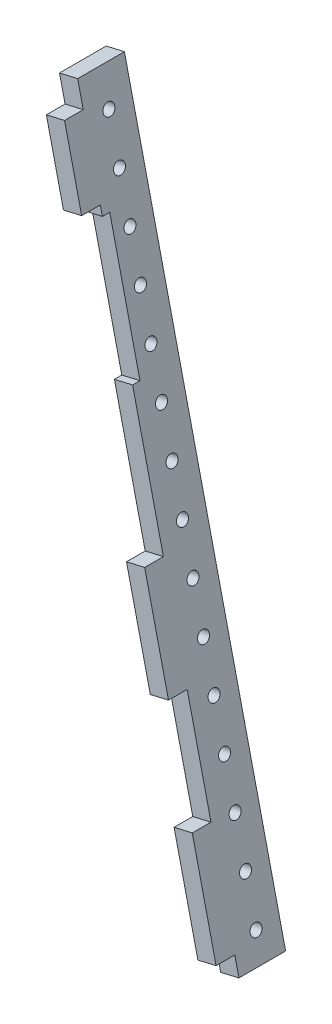
SolidWorks part; units mm, degrees
ref_plane "Front Plane" through (0, 0, 0) normal (0, 0, 1) x (1, 0, 0)
ref_plane "Top Plane" through (0, 0, 0) normal (0, 1, 0) x (1, 0, 0)
ref_plane "Right Plane" through (0, 0, 0) normal (1, 0, 0) x (0, 0, -1)
sketch "Sketch1" plane through (0, 0, 0) normal (0, 0, 1) x (1, 0, 0)
  line L0 (-117.4836, 1583.6084) -> (-107.584, 1585.8939) construction
  line L1 (-81.7027, 1473.7898) -> (-94.6434, 1529.8418) construction
  line L2 (-91.6023, 1471.5043) -> (-81.7027, 1473.7898) construction
  line L3 (-91.6023, 1471.5043) -> (-104.543, 1527.5563) construction
  line L4 (-104.543, 1527.5563) -> (-94.6434, 1529.8418) construction
  line L5 (-120.5247, 1641.946) -> (-107.584, 1585.8939) construction
  line L6 (-130.4243, 1639.6605) -> (-117.4836, 1583.6084) construction
  line L7 (-130.4243, 1639.6605) -> (-120.5247, 1641.946) construction
  line L8 (-120.5247, 1641.946) -> (-107.584, 1585.8939)
  line L9 (-130.4243, 1639.6605) -> (-120.5247, 1641.946)
  line L10 (-130.4243, 1639.6605) -> (-117.4836, 1583.6084)
  line L11 (-117.4836, 1583.6084) -> (-107.584, 1585.8939)
  line L12 (-104.543, 1527.5563) -> (-94.6434, 1529.8418)
  line L13 (-91.6023, 1471.5043) -> (-81.7027, 1473.7898)
  line L14 (-91.6023, 1471.5043) -> (-104.543, 1527.5563)
  line L15 (-81.7027, 1473.7898) -> (-94.6434, 1529.8418)
  line L16 (-81.7027, 1473.7898) -> (-173.3401, 1870.7149) construction
  line L17 (-91.6023, 1471.5043) -> (-181.4804, 1860.8088) construction
  line L18 (-164.7068, 1788.1545) -> (-154.8072, 1790.44)
  line L19 (-173.9916, 1828.3716) -> (-164.0921, 1830.6571)
  line L20 (-173.9916, 1828.3716) -> (-164.7068, 1788.1545)
  line L21 (-164.0921, 1830.6571) -> (-154.8072, 1790.44)
  point P4 (-159.757, 1789.2972)
  dimension "D1" = 152.4
  dimension "D2" = 41.275
extrude "Boss-Extrude1" add sketch "Sketch1" against normal blind 10.16
sketch "Sketch2" plane through (0, 0, -10.16) normal (0, 0, -1) x (-1, 0, 0)
  line L0 (177.0163, 1841.4726) -> (89.3528, 1461.7606)
  line L1 (130.4243, 1639.6605) -> (117.4836, 1583.6084) construction
  line L2 (167.1167, 1843.7581) -> (79.4532, 1464.0461)
  line L3 (79.4532, 1464.0461) -> (89.3528, 1461.7606)
  line L4 (167.1167, 1843.7581) -> (177.0163, 1841.4726)
  line L5 (91.6023, 1471.5043) -> (81.7027, 1473.7898) construction
  dimension "D1" = 10.16
  dimension "D2" = 389.7
  dimension "D3" = 10
extrude "Boss-Extrude2" add sketch "Sketch2" along normal blind 25.4
sketch "Sketch3" plane through (235.5655, 54.3846, 0) normal (-0.9744, -0.225, 0) x (0, 0, 1)
  line L0 (-22.86, 1834.0958) -> (-22.86, 1444.3958) construction
  line L1 (-35.56, 1834.0958) -> (-10.16, 1834.0958) construction
  line L2 (-35.56, 1444.3958) -> (-10.16, 1444.3958) construction
  line L3 (-10.16, 1626.9752) -> (-10.16, 1779.3752) construction
  line L4 (-14.16, 1774.3752) -> (15.0587, 1774.3752)
  line L5 (-14.16, 1774.3752) -> (-14.16, 1701.3752)
  line L6 (-14.16, 1701.3752) -> (15.0587, 1701.3752)
  line L7 (15.0587, 1774.3752) -> (15.0587, 1701.3752)
  line L8 (-10.16, 1779.3752) -> (0, 1779.3752) construction
  circle A0 centre (-22.86, 1459.3958) radius 3.175
  circle A1 centre (-22.86, 1484.7958) radius 3.175
  circle A2 centre (-22.86, 1510.1958) radius 3.175
  circle A3 centre (-22.86, 1535.5958) radius 3.175
  circle A4 centre (-22.86, 1560.9958) radius 3.175
  circle A5 centre (-22.86, 1586.3958) radius 3.175
  circle A6 centre (-22.86, 1611.7958) radius 3.175
  circle A7 centre (-22.86, 1637.1958) radius 3.175
  circle A8 centre (-22.86, 1662.5958) radius 3.175
  circle A9 centre (-22.86, 1687.9958) radius 3.175
  circle A10 centre (-22.86, 1713.3958) radius 3.175
  circle A11 centre (-22.86, 1738.7958) radius 3.175
  circle A12 centre (-22.86, 1764.1958) radius 3.175
  circle A13 centre (-22.86, 1789.5958) radius 3.175
  circle A14 centre (-22.86, 1814.9958) radius 3.175
  point P44 (-5.08, 1779.3752)
  dimension "D1" = 6.35
  dimension "D2" = 15
  dimension "D4" = 4
  dimension "D5" = 5
  dimension "D6" = 78
  dimension "D3" = 15
extrude "Cut-Extrude1" cut sketch "Sketch3" against normal through all
